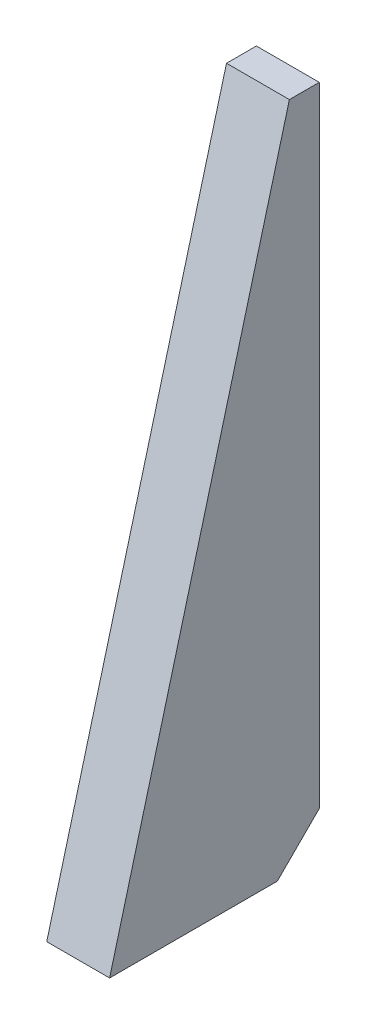
SolidWorks part; units mm, degrees
ref_plane "Front Plane" through (0, 0, 0) normal (0, 0, 1) x (1, 0, 0)
ref_plane "Top Plane" through (0, 0, 0) normal (0, 1, 0) x (1, 0, 0)
ref_plane "Right Plane" through (0, 0, 0) normal (1, 0, 0) x (0, 0, -1)
sketch "Sketch1" plane through (0, 0, 0) normal (1, 0, 0) x (0, 0, -1)
  line L0 (0, 0) -> (50, 0)
  line L1 (50, 0) -> (50, 160)
  line L2 (0, 0) -> (42.8719, 160)
  line L3 (50, 160) -> (42.8719, 160)
  dimension "D1" = 50
  dimension "D2" = 160
  dimension "D3" = 75
extrude "Boss-Extrude1" add sketch "Sketch1" along normal blind 15
chamfer "Chamfer1" distance 10 angle 45 1 edges at (7.5, 0, -50)
